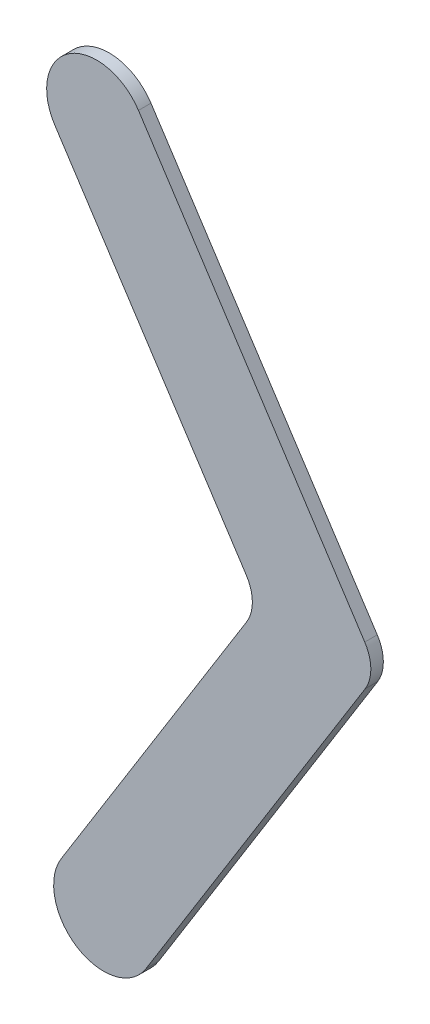
SolidWorks part; units mm, degrees
material "Custom Plastic"
ref_plane "X-Y Datum" through (0, 0, 0) normal (0, 0, 1) x (1, 0, 0)
ref_plane "X-Z Datum" through (0, 0, 0) normal (0, 1, 0) x (1, 0, 0)
ref_plane "Y-Z Datum" through (0, 0, 0) normal (1, 0, 0) x (0, 0, -1)
sketch "Sketch1" plane through (0, 0, 0) normal (0, 0, 1) x (1, 0, 0)
  line L7 (0, 0) -> (-15.8597, -25.4651)
  line L10 (9.485, 0.0969) -> (-9.069, -29.6943)
  line L14 (9.485, 0.0969) -> (0, 0) construction
  line L15 (0, 0) -> (-28.584, 0.936) construction
  line L18 (0, 0) -> (-16.3766, 25.1358)
  line L19 (9.485, 0.0969) -> (-9.6737, 29.5029)
  arc A2 (-15.8597, -25.4651) -> (-9.069, -29.6943) centre (-12.4644, -27.5797) ccw
  arc A4 (-16.3766, 25.1358) -> (-9.6737, 29.5029) centre (-13.0251, 27.3193) cw
  dimension "D1" = 59.961
  dimension "D3" = 8
extrude "Boss-Extrude1" add sketch "Sketch1" along normal blind 1
fillet "Fillet2" radius 3 2 edges at (9.485, 0.0969, 0.5) (0, 0, 0.5)
